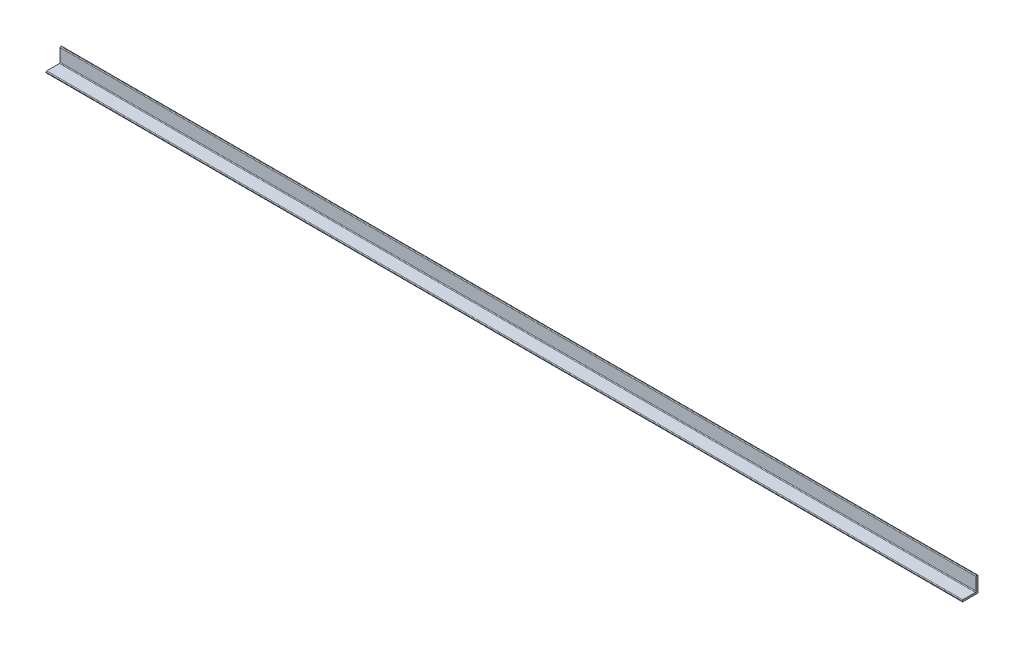
SolidWorks part; units mm, degrees
ref_plane "Front Plane" through (0, 0, 0) normal (0, 0, 1) x (1, 0, 0)
ref_plane "Top Plane" through (0, 0, 0) normal (0, 1, 0) x (1, 0, 0)
ref_plane "Right Plane" through (0, 0, 0) normal (1, 0, 0) x (0, 0, -1)
sketch "Sketch1" plane through (0, 0, 0) normal (0, 1, 0) x (1, 0, 0)
  line L1 (-650, 11.25) -> (650, 11.25)
  line L2 (-650, 11.25) -> (-650, -11.25)
  line L3 (-650, -11.25) -> (650, -11.25)
  line L4 (650, 11.25) -> (650, -11.25)
  line L5 (-650, 11.25) -> (650, -11.25) construction
  line L6 (-650, -11.25) -> (650, 11.25) construction
  point P0 (0, 0)
  dimension "D1" = 1300
  dimension "D2" = 22.5
extrude "Boss-Extrude1" add sketch "Sketch1" along normal blind 2.5
sketch "Sketch2" plane through (0, 2.5, 0) normal (0, 1, 0) x (1, 0, 0)
  line L0 (650, -11.25) -> (650, 11.25) construction
  line L1 (-650, 11.25) -> (650, 11.25)
  line L2 (-650, 11.25) -> (-650, 8.75)
  line L3 (-650, 8.75) -> (650, 8.75)
  line L4 (650, 11.25) -> (650, 8.75)
  dimension "D1" = 2.5
extrude "Boss-Extrude2" add sketch "Sketch2" along normal blind 20
fillet "Fillet1" radius 1 6 edges at (0, 0, -11.25) (0, 0, 11.25) (0, 2.5, 11.25) (0, 2.5, -8.75) (0, 22.5, -8.75) (0, 22.5, -11.25)
